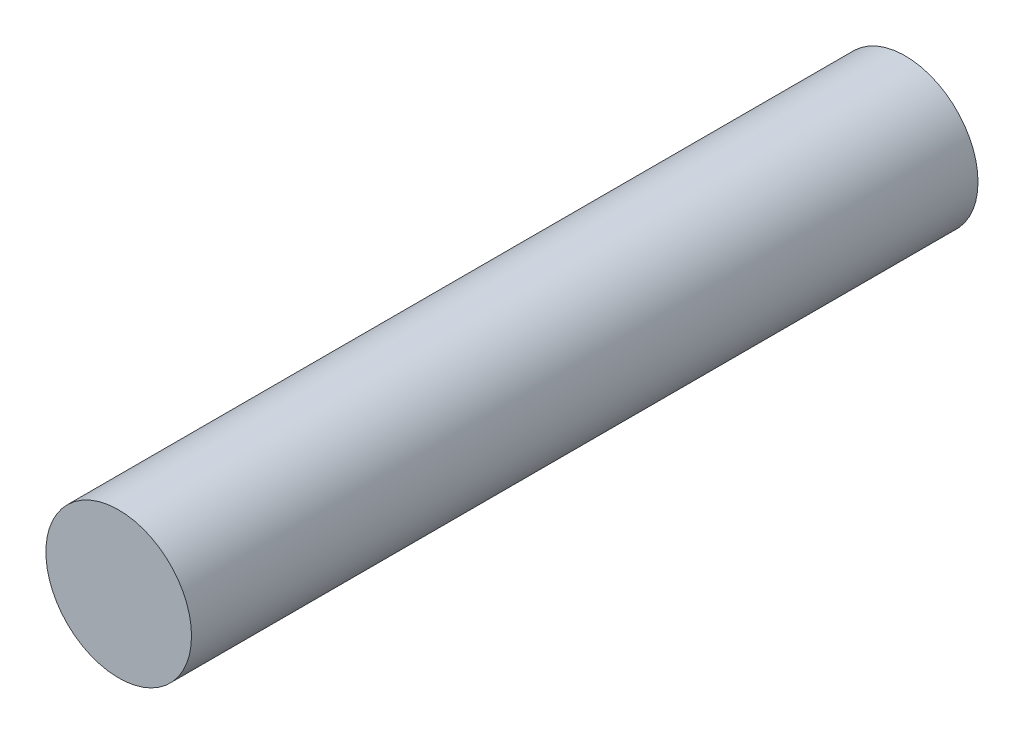
SolidWorks part; units mm, degrees
ref_plane "Plan de face" through (0, 0, 0) normal (0, 0, 1) x (1, 0, 0)
ref_plane "Plan de dessus" through (0, 0, 0) normal (0, 1, 0) x (1, 0, 0)
ref_plane "Plan de droite" through (0, 0, 0) normal (1, 0, 0) x (0, 0, -1)
sketch "Esquisse1" plane through (0, 0, 0) normal (0, 0, 1) x (1, 0, 0)
  circle A0 centre (0, 0) radius 2.5
  dimension "D1" = 5
extrude "Boss.-Extru.1" add sketch "Esquisse1" along normal blind 27
